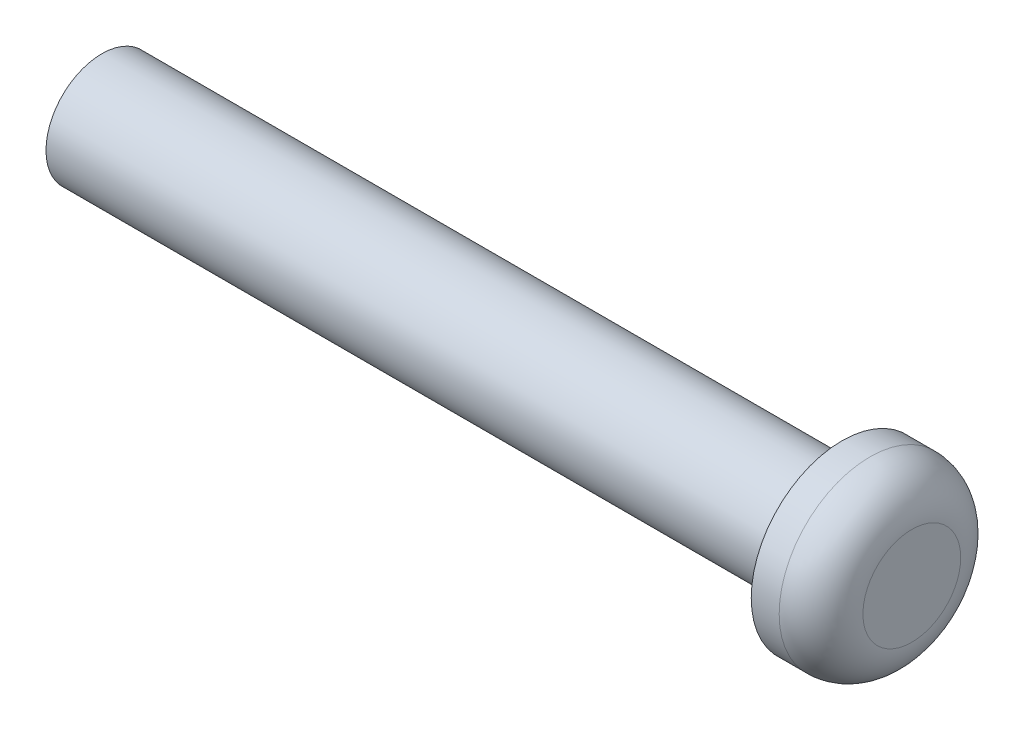
SolidWorks part; units mm, degrees
ref_plane "Front Plane" through (0, 0, 0) normal (0, 0, 1) x (1, 0, 0)
ref_plane "Top Plane" through (0, 0, 0) normal (0, 1, 0) x (1, 0, 0)
ref_plane "Right Plane" through (0, 0, 0) normal (1, 0, 0) x (0, 0, -1)
sketch "Sketch1" plane through (0, 0, 0) normal (1, 0, 0) x (0, 0, -1)
  circle A0 centre (0, 0) radius 6.5
extrude "Boss-Extrude1" add sketch "Sketch1" along normal blind 5
sketch "Sketch2" plane through (0, 0, 0) normal (-1, 0, 0) x (0, 0, 1)
  circle A0 centre (0, 0) radius 4
extrude "Boss-Extrude2" add sketch "Sketch2" along normal blind 53
fillet "Fillet1" radius 3 1 edges at (5, 0, -6.5)
